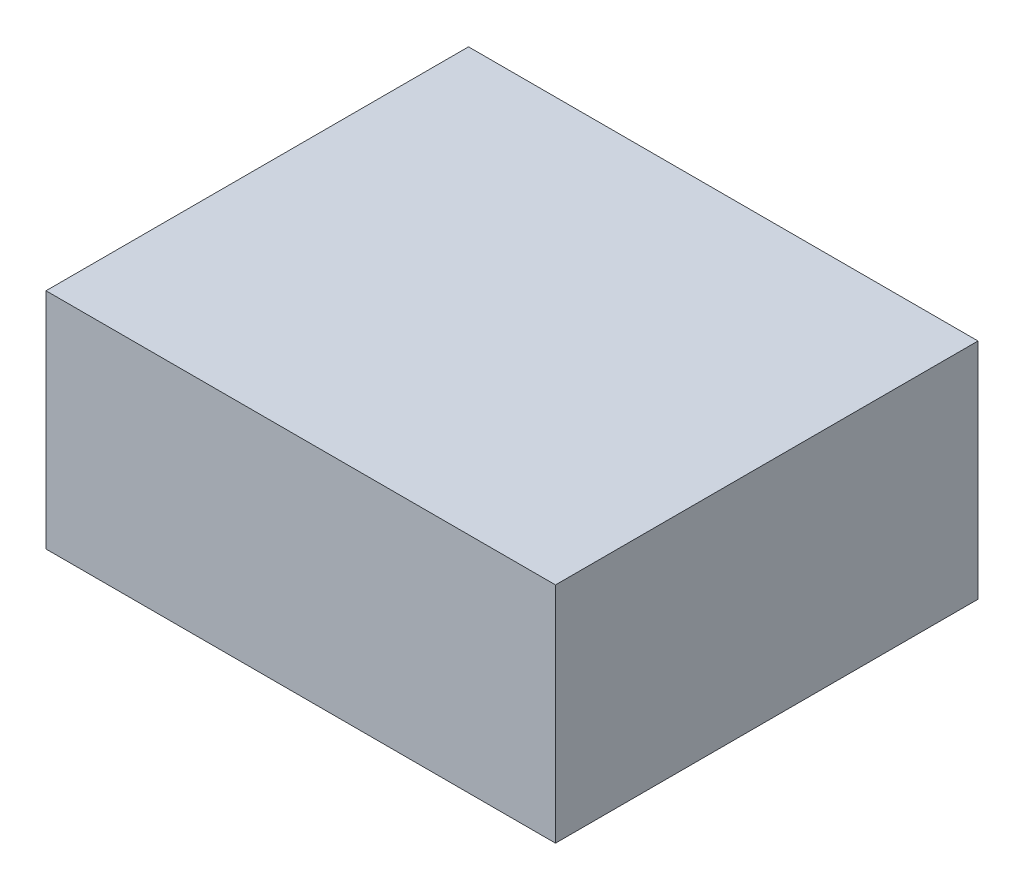
SolidWorks part; units mm, degrees
ref_plane "Front Plane" through (0, 0, 0) normal (0, 0, 1) x (1, 0, 0)
ref_plane "Top Plane" through (0, 0, 0) normal (0, 1, 0) x (1, 0, 0)
ref_plane "Right Plane" through (0, 0, 0) normal (1, 0, 0) x (0, 0, -1)
sketch "Sketch1" plane through (0, 0, 0) normal (0, 1, 0) x (1, 0, 0)
  line L1 (0, 0) -> (4.1, 0)
  line L2 (0, 0) -> (0, 3.4)
  line L3 (0, 3.4) -> (4.1, 3.4)
  line L4 (4.1, 0) -> (4.1, 3.4)
  dimension "D1" = 4.1
  dimension "D2" = 3.4
extrude "Boss-Extrude1" add sketch "Sketch1" along normal blind 1.8
